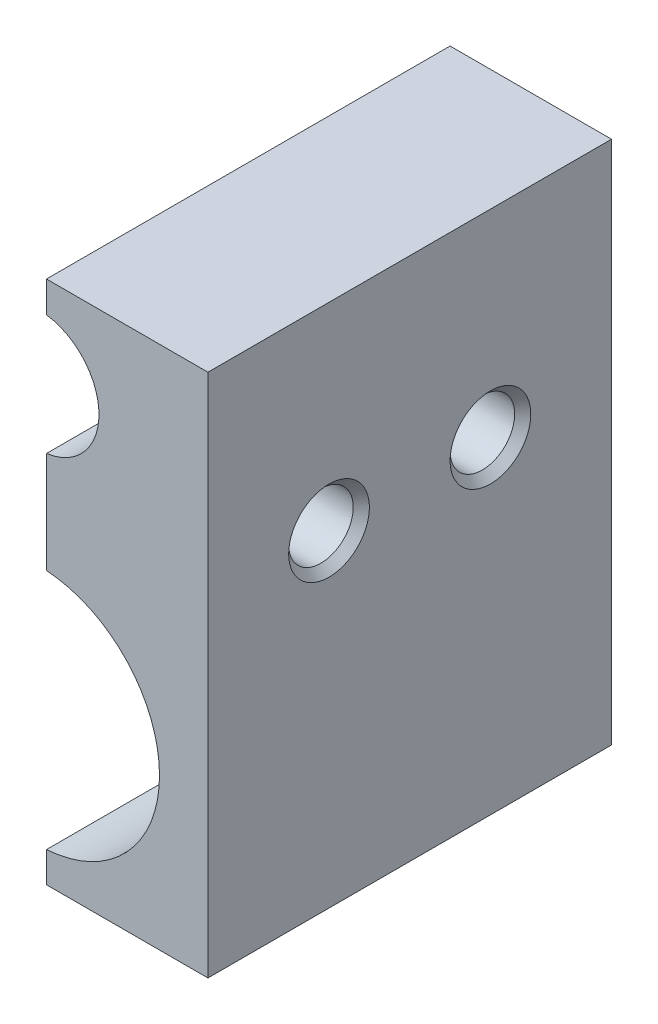
SolidWorks part; units mm, degrees
material "Custom Plastic"
ref_plane "Front Plane" through (0, 0, 0) normal (0, 0, 1) x (1, 0, 0)
ref_plane "Top Plane" through (0, 0, 0) normal (0, 1, 0) x (1, 0, 0)
ref_plane "Right Plane" through (0, 0, 0) normal (1, 0, 0) x (0, 0, -1)
sketch "Sketch1" plane through (0, 0, 0) normal (0, 0, 1) x (1, 0, 0)
  line L0 (0, 3.7833) -> (0, 0)
  line L1 (0, 0) -> (20, 0)
  line L3 (0, 65) -> (20, 65)
  line L4 (20, 0) -> (20, 65)
  line L5 (0, 65) -> (0, 61.1496)
  line L6 (0, 65) -> (0, 61.1496)
  line L7 (0, 46.2835) -> (0, 33.7165)
  line L8 (0, 3.7833) -> (0, 0)
  line L9 (0, 46.2835) -> (0, 33.7165)
  arc A0 (0, 61.1496) -> (0, 46.2835) centre (-1, 53.7165) cw
  arc A1 (0, 3.7833) -> (0, 33.7165) centre (-1, 18.7499) ccw
  dimension "D3" = 7.5
  dimension "D6" = 20
  dimension "D1" = 15
  dimension "D2" = 65
  dimension "D4" = 20
  dimension "D5" = 3.8504
  dimension "D7" = 1
  dimension "D8" = 1
extrude "Boss-Extrude1" add sketch "Sketch1" along normal blind 50
sketch "Sketch2" plane through (20, 0, 0) normal (1, 0, 0) x (0, 0, -1)
  line L0 (-45, 40.5051) -> (-5, 40.5051) construction
  line L3 (-45, 40.5051) -> (-25, 40.5051) construction
  line L4 (-25, 40.5051) -> (-35, 40.5051) construction
  line L5 (-25, 40.5051) -> (-5, 40.5051) construction
  line L6 (-5, 40.5051) -> (-15, 40.5051) construction
  circle A0 centre (-35, 40.5051) radius 4
  circle A1 centre (-15, 40.5051) radius 4
  point P2 (-20, 40)
  point P3 (0, 0)
  point P4 (-10, 40)
  point P5 (-40, 40)
  dimension "D1" = 8
  dimension "D2" = 8
  dimension "D3" = 25
  dimension "D4" = 40
  dimension "D5" = 25
extrude "Cut-Extrude1" cut sketch "Sketch2" against normal up to surface (20 mm away) up to face at (0, 40, 25)
chamfer "Chamfer1" distance 1 angle 45 2 edges at (20, 40.5051, 11) (20, 40.5051, 31)
